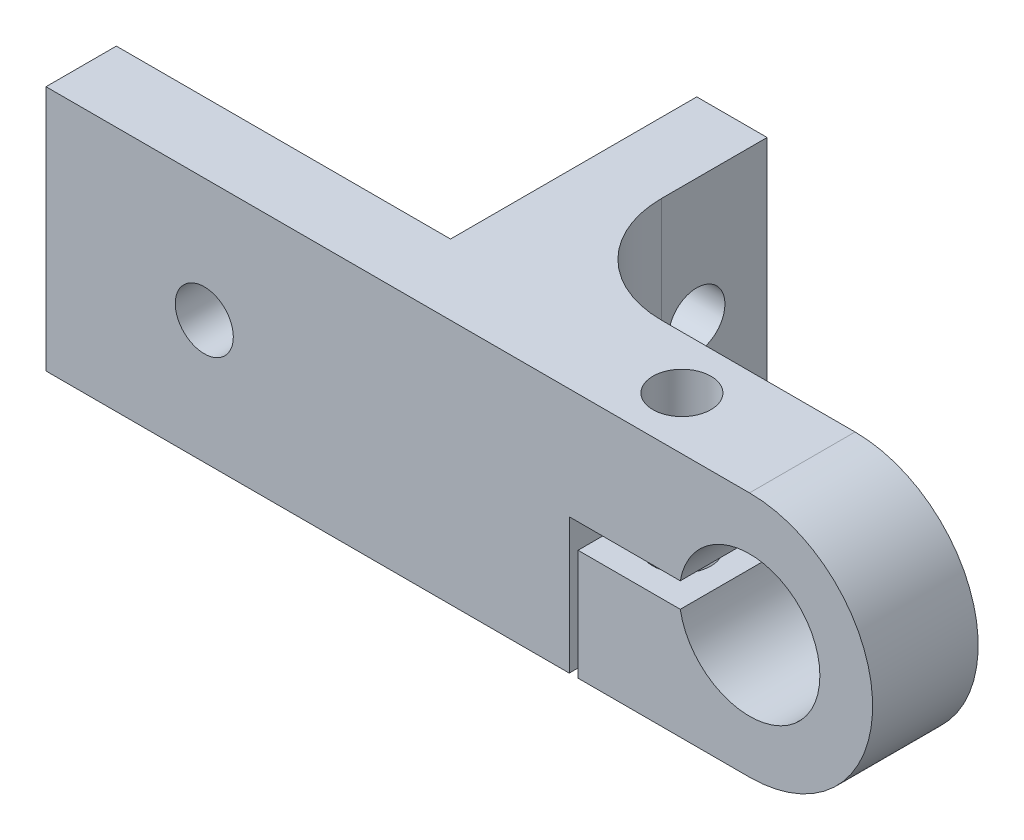
SolidWorks part; units mm, degrees
ref_plane "Plano frontal" through (0, 0, 0) normal (0, 0, 1) x (1, 0, 0)
ref_plane "Plano superior" through (0, 0, 0) normal (0, 1, 0) x (1, 0, 0)
ref_plane "Plano direito" through (0, 0, 0) normal (1, 0, 0) x (0, 0, -1)
sketch "Esboço2" plane through (0, 0, 0) normal (0, 0, 1) x (1, 0, 0)
  line L0 (0, 7) -> (-40, 7)
  line L1 (-40, 7) -> (-40, -7)
  line L2 (-40, -7) -> (-10.25, -7)
  line L3 (-4, 0) -> (-10, 0) construction
  line L4 (-10, 0) -> (-10, -7) construction
  line L5 (-3.9383, 0.7) -> (-10.25, 0.7)
  line L6 (-10.25, 0.7) -> (-10.25, -7)
  line L7 (-3.9383, -0.7) -> (-9.75, -0.7)
  line L8 (-9.75, -0.7) -> (-9.75, -7)
  line L11 (-9.75, -7) -> (0, -7)
  arc A0 (-3.9383, -0.7) -> (-3.9383, 0.7) centre (0, 0) ccw
  arc A1 (0, -7) -> (0, 7) centre (0, 0) ccw
  circle A2 centre (-31, 0) radius 1.65
  point P20 (-40, 0)
  dimension "D1" = 8
  dimension "D3" = 7
  dimension "D8" = 3.3
  dimension "D2" = 10
  dimension "D6" = 30
  dimension "D7" = 9
  dimension "D4" = 0.7
  dimension "D5" = 0.7
  dimension "D9" = 0.5
extrude "Ressalto-extrusão1" add sketch "Esboço2" along normal blind 18
sketch "Esboço3" plane through (0, -7, 0) normal (0, -1, 0) x (1, 0, 0)
  line L0 (-40, 14) -> (-21, 14)
  line L1 (-40, 18) -> (-40, 0) construction
  line L2 (-21, 14) -> (-21, 0)
  line L3 (-40, 0) -> (-10.25, 0) construction
  line L4 (-21, 0) -> (-40, 0)
  line L5 (-40, 0) -> (-40, 14)
  line L6 (7, 12) -> (-11, 12)
  line L7 (7, 0) -> (7, 18) construction
  line L8 (-17, 0) -> (7, 0)
  line L9 (7, 0) -> (7, 12)
  line L10 (-17, 0) -> (-17, 6)
  line L11 (-40, 18) -> (-10.25, 18) construction
  line L12 (-9.75, 18) -> (0, 18) construction
  line L13 (-3.9383, 18) -> (-9.75, 18) construction
  line L14 (-2.8316, 18) -> (-2.8316, 12) construction
  arc A0 (-17, 6) -> (-11, 12) centre (-11, 6) cw
  circle A1 centre (-6.8441, 15) radius 1.65
  point P10 (-2.8316, 15)
  point P28 (-6.8441, 18)
  dimension "D1" = 6
  dimension "D6" = 3.3
  dimension "D2" = 4
  dimension "D3" = 6
  dimension "D4" = 4
  dimension "D5" = 19
extrude "Corte-extrusão1" cut sketch "Esboço3" against normal through all and the other way through all
sketch "Esboço4" plane through (-21, 0, 0) normal (-1, 0, 0) x (0, 0, 1)
  line L0 (14, 7) -> (14, -7) construction
  line L1 (0, 7) -> (0, -7) construction
  circle A0 centre (4, 0) radius 1.6
  point P7 (0, 0)
  dimension "D2" = 3.2
  dimension "D1" = 10
extrude "Corte-extrusão2" cut sketch "Esboço4" against normal blind 18
